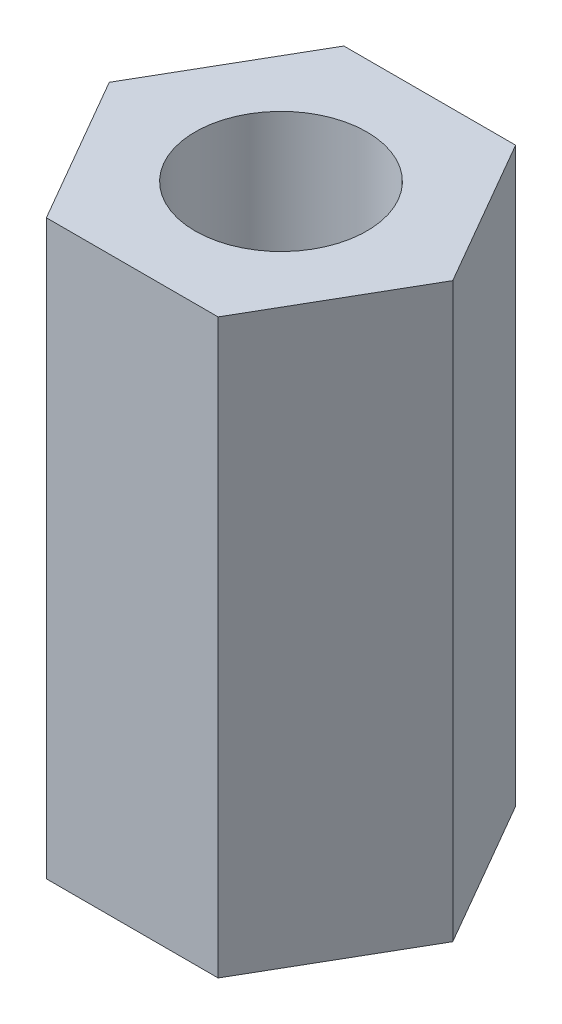
SolidWorks part; units mm, degrees
ref_plane "Front Plane" through (0, 0, 0) normal (0, 0, 1) x (1, 0, 0)
ref_plane "Top Plane" through (0, 0, 0) normal (0, 1, 0) x (1, 0, 0)
ref_plane "Right Plane" through (0, 0, 0) normal (1, 0, 0) x (0, 0, -1)
sketch "Sketch1" plane through (0, 0, 0) normal (0, 1, 0) x (1, 0, 0)
  line L0 (-3, 0) -> (3, 0) construction
  line L1 (-1.5, 2.5981) -> (-3, 0)
  line L2 (-3, 0) -> (-1.5, -2.5981)
  line L3 (-1.5, -2.5981) -> (1.5, -2.5981)
  line L4 (1.5, -2.5981) -> (3, 0)
  line L5 (3, 0) -> (1.5, 2.5981)
  line L6 (1.5, 2.5981) -> (-1.5, 2.5981)
  circle A0 centre (0, 0) radius 1.5
  circle A2 centre (0, 0) radius 2.5981 construction
  dimension "D1" = 3
  dimension "D2" = 3
extrude "Boss-Extrude1" add sketch "Sketch1" along normal blind 10
